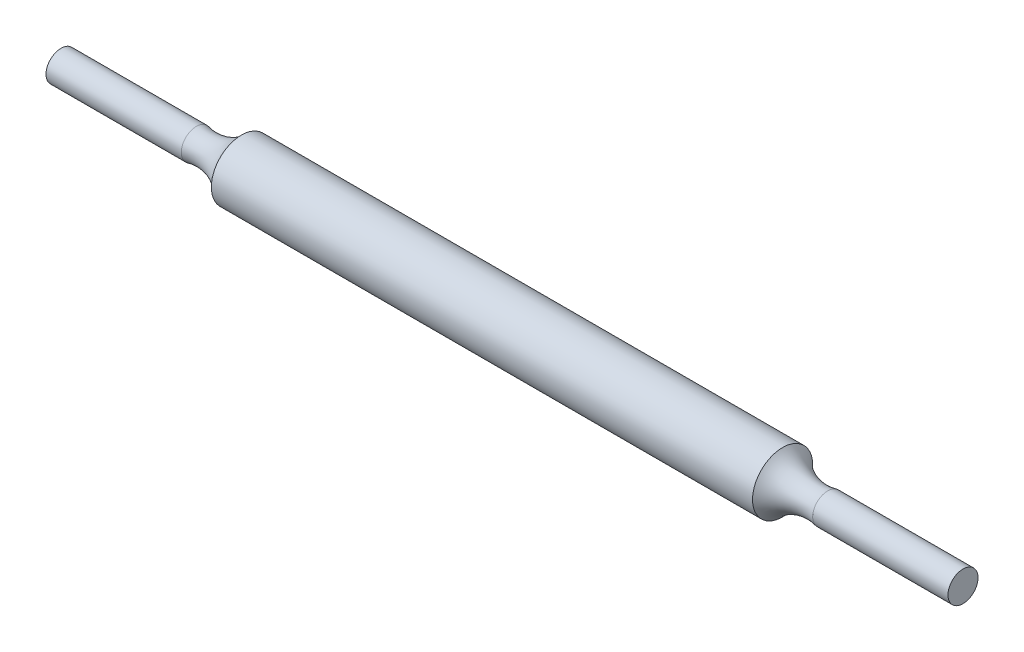
SolidWorks part; units mm, degrees
ref_plane "Front Plane" through (0, 0, 0) normal (0, 0, 1) x (1, 0, 0)
ref_plane "Top Plane" through (0, 0, 0) normal (0, 1, 0) x (1, 0, 0)
ref_plane "Right Plane" through (0, 0, 0) normal (1, 0, 0) x (0, 0, -1)
sketch "Sketch2" plane through (0, 0, 0) normal (0, 0, 1) x (1, 0, 0)
  line L0 (-762, 0) -> (762, 0)
  line L1 (762, 0) -> (762, 25.4)
  line L2 (762, 25.4) -> (533.4, 25.4)
  line L3 (457.2, 50.8) -> (-457.2, 50.8)
  line L5 (-762, 0) -> (-762, 25.4)
  line L6 (-762, 25.4) -> (-533.4, 25.4)
  arc A0 (457.2, 50.8) -> (533.4, 25.4) centre (515.7781, 99.5344) ccw
  arc A1 (-457.2, 50.8) -> (-533.4, 25.4) centre (-515.7781, 99.5344) cw
  point P3 (0, 50.8)
  point P10 (0, 0)
  point P12 (0, 0)
  point P17 (0, 50.8)
  dimension "D4" = 50.8
  dimension "D1" = 762
  dimension "D2" = 25.4
  dimension "D3" = 228.6
  dimension "D5" = 76.2
revolve "Revolve4" add sketch "Sketch2" angle 360 about L0
